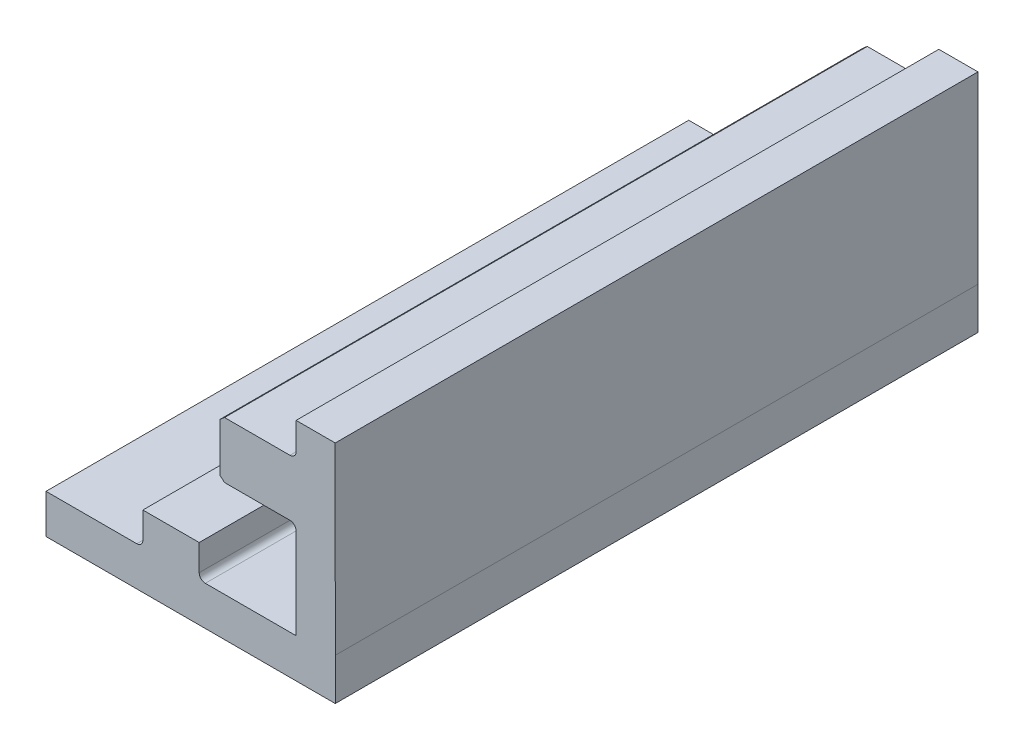
SolidWorks part; units mm, degrees
ref_plane "Front Plane" through (0, 0, 0) normal (0, 0, 1) x (1, 0, 0)
ref_plane "Top Plane" through (0, 0, 0) normal (0, 1, 0) x (1, 0, 0)
ref_plane "Right Plane" through (0, 0, 0) normal (1, 0, 0) x (0, 0, -1)
ref_plane "Plane1" through (0, 0, -3683) normal (0, 0, -1) x (-1, 0, 0)
sketch "Sketch1" plane through (0, 0, -3683) normal (0, 0, -1) x (-1, 0, 0)
  line L0 (7.9453, 3.5889) -> (-1.1987, 3.5889)
  line L1 (-1.8337, 4.2239) -> (-1.8337, 5.7479)
  line L2 (-1.1987, 6.3829) -> (1.6216, 6.3829)
  line L3 (1.6216, 6.3829) -> (1.6216, 6.8909)
  line L4 (1.6216, 6.8909) -> (-2.2147, 11.4629)
  line L5 (-2.2147, 11.4629) -> (-7.2947, 11.4629)
  line L6 (-7.2947, 11.4629) -> (-11.1311, 6.8909)
  line L7 (-11.1311, 6.8909) -> (-11.1311, 6.3829)
  line L8 (-11.1311, 6.3829) -> (-8.3107, 6.3829)
  line L9 (-7.6757, 5.7479) -> (-7.6757, 4.2239)
  line L10 (-8.3107, 3.5889) -> (-17.4547, 3.5889)
  line L11 (-17.7279, 3.8588) -> (-17.7284, 13.0024)
  line L12 (-17.4548, -0.4751) -> (7.9452, -0.4751)
  line L13 (-17.0929, 13.6378) -> (-15.5689, 13.6378)
  line L29 (-17.4547, 3.5889) -> (-17.7279, 3.5889)
  line L30 (-17.4548, -0.4751) -> (-17.7279, -0.4751)
  line L32 (8.2155, 3.5889) -> (8.2155, -0.4751)
  line L34 (8.2155, 3.5889) -> (7.9453, 3.5889)
  line L35 (8.2155, -0.4751) -> (7.9452, -0.4751)
  line L36 (-14.9339, 13.0028) -> (-14.9339, 10.1825)
  line L37 (-14.9339, 10.1825) -> (-14.4259, 10.1825)
  line L38 (-14.4259, 10.1825) -> (-9.8539, 14.0188)
  line L39 (-9.8539, 14.0188) -> (-9.8539, 19.0988)
  line L40 (-9.8539, 19.0988) -> (-14.4259, 22.9352)
  line L41 (-14.4259, 22.9352) -> (-14.9339, 22.9352)
  line L42 (-14.9339, 22.9352) -> (-14.9339, 20.1148)
  line L43 (-15.5689, 19.4798) -> (-17.0929, 19.4798)
  line L44 (-17.7287, 20.1156) -> (-17.7288, 22.9352)
  line L45 (-21.7872, 22.9352) -> (-21.7919, 3.8591)
  line L49 (-17.7288, 22.9352) -> (-21.7872, 22.9352)
  line L51 (-17.7279, 3.5889) -> (-17.7279, 3.8588)
  line L52 (-21.7919, 3.5889) -> (-21.7919, 3.8591)
  line L54 (-17.7279, -0.4751) -> (-21.7919, -0.4751)
  line L56 (-21.7919, -0.4751) -> (-21.7919, 3.5889)
  arc A0 (-1.1987, 3.5889) -> (-1.8337, 4.2239) centre (-1.1987, 4.2239) cw
  arc A1 (-1.8337, 5.7479) -> (-1.1987, 6.3829) centre (-1.1987, 5.7479) cw
  arc A2 (-8.3107, 6.3829) -> (-7.6757, 5.7479) centre (-8.3107, 5.7479) cw
  arc A3 (-7.6757, 4.2239) -> (-8.3107, 3.5889) centre (-8.3107, 4.2239) cw
  arc A4 (-17.7284, 13.0024) -> (-17.0929, 13.6378) centre (-17.0929, 13.0024) cw
  arc A5 (-15.5689, 13.6378) -> (-14.9339, 13.0028) centre (-15.5689, 13.0028) cw
  arc A6 (-14.9339, 20.1148) -> (-15.5689, 19.4798) centre (-15.5689, 20.1148) cw
  arc A7 (-17.0929, 19.4798) -> (-17.7287, 20.1156) centre (-17.0929, 20.1156) cw
extrude "Boss-Extrude1" add sketch "Sketch1" along normal blind 66.675
sketch "Sketch2" plane through (0, 0, -3683) normal (0, 0, 1) x (1, 0, 0)
  line L0 (11.1311, 6.8909) -> (11.1311, 6.3829) construction
  line L1 (11.1311, 6.3829) -> (8.3107, 6.3829) construction
  line L2 (7.2947, 11.4629) -> (11.1311, 6.8909) construction
  line L3 (4.7547, 11.4629) -> (4.7547, -3.7872) construction
  line L4 (7.6757, 5.7479) -> (7.6757, 4.2239) construction
  line L5 (11.1311, 6.8909) -> (11.1311, 6.3829)
  line L6 (11.1311, 6.3829) -> (8.3107, 6.3829)
  line L7 (7.6757, 11.0088) -> (11.1311, 6.8909)
  line L8 (2.2147, 11.4629) -> (7.2947, 11.4629) construction
  line L9 (7.6757, 5.7479) -> (7.6757, 11.0088)
  line L10 (1.8337, 5.7479) -> (1.8337, 11.0088)
  line L11 (1.8337, 11.0088) -> (-1.6216, 6.8909)
  line L12 (-1.6216, 6.3829) -> (1.1987, 6.3829)
  line L13 (-1.6216, 6.8909) -> (-1.6216, 6.3829)
  arc A0 (8.3107, 6.3829) -> (7.6757, 5.7479) centre (8.3107, 5.7479) ccw construction
  arc A1 (8.3107, 6.3829) -> (7.6757, 5.7479) centre (8.3107, 5.7479) ccw
  arc A2 (1.1987, 6.3829) -> (1.8337, 5.7479) centre (1.1987, 5.7479) cw
extrude "Cut-Extrude1" cut sketch "Sketch2" against normal up to next
sketch "Sketch3" plane through (0, 0, -3683) normal (0, 0, 1) x (1, 0, 0)
  line L0 (15.5689, 19.4798) -> (17.0929, 19.4798) construction
  line L1 (14.9339, 22.9352) -> (14.9339, 20.1148) construction
  line L2 (14.4259, 22.9352) -> (14.9339, 22.9352) construction
  line L3 (9.8539, 19.0988) -> (14.4259, 22.9352) construction
  line L4 (15.5689, 19.4798) -> (10.308, 19.4798)
  line L5 (14.9339, 22.9352) -> (14.9339, 20.1148)
  line L6 (14.4259, 22.9352) -> (14.9339, 22.9352)
  line L7 (10.308, 19.4798) -> (14.4259, 22.9352)
  line L8 (9.8539, 16.5588) -> (24.7491, 16.5588) construction
  line L9 (9.8539, 14.0188) -> (9.8539, 19.0988) construction
  line L10 (10.308, 13.6378) -> (14.4259, 10.1825)
  line L11 (14.4259, 10.1825) -> (14.9339, 10.1825)
  line L12 (14.9339, 10.1825) -> (14.9339, 13.0028)
  line L13 (15.5689, 13.6378) -> (10.308, 13.6378)
  arc A0 (14.9339, 20.1148) -> (15.5689, 19.4798) centre (15.5689, 20.1148) ccw construction
  arc A1 (14.9339, 20.1148) -> (15.5689, 19.4798) centre (15.5689, 20.1148) ccw
  arc A2 (14.9339, 13.0028) -> (15.5689, 13.6378) centre (15.5689, 13.0028) cw
extrude "Cut-Extrude2" cut sketch "Sketch3" against normal up to next
sketch "Sketch6" plane through (0, 0, -3749.675) normal (0, 0, -1) x (-1, 0, 0)
  line L0 (-1.8337, 4.2239) -> (-1.8337, 11.0088) construction
  line L1 (-1.8337, 6.9354) -> (-7.6757, 6.9354)
  line L2 (-1.8337, 6.9354) -> (-1.8337, 11.8138)
  line L3 (-1.8337, 11.8138) -> (-7.6757, 11.8138)
  line L4 (-7.6757, 6.9354) -> (-7.6757, 11.8138)
extrude "Cut-Extrude4" cut sketch "Sketch6" against normal through all
